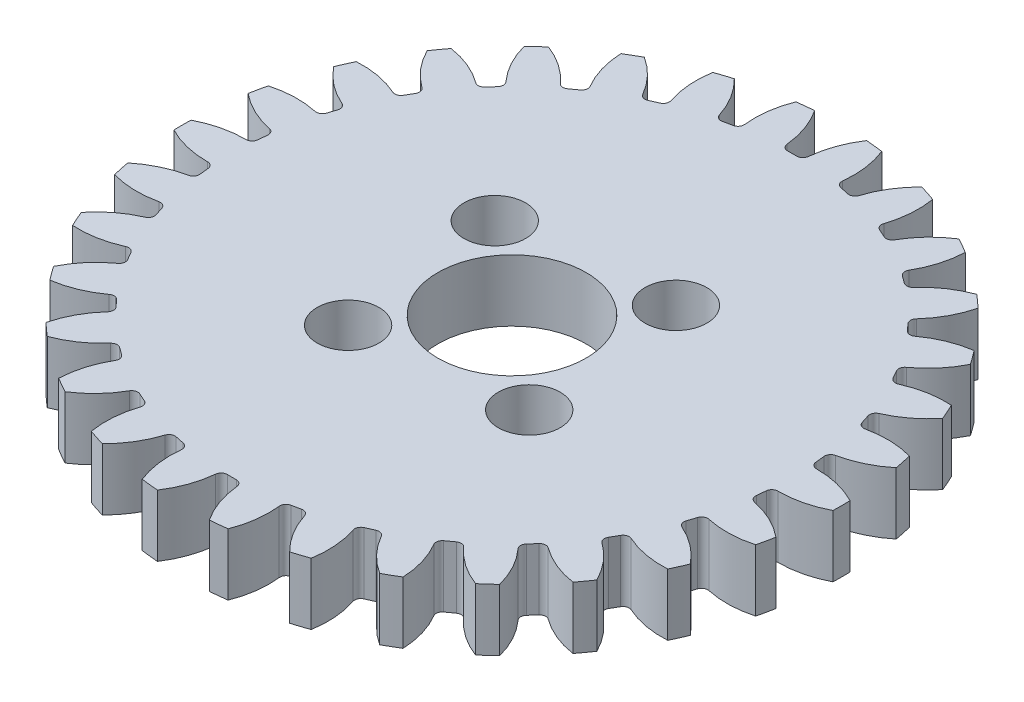
SolidWorks part; units mm, degrees
ref_plane "Alzado" through (0, 0, 0) normal (0, 0, 1) x (1, 0, 0)
ref_plane "Planta" through (0, 0, 0) normal (0, 1, 0) x (1, 0, 0)
ref_plane "Vista lateral" through (0, 0, 0) normal (1, 0, 0) x (0, 0, -1)
sketch "Croquis1" plane through (0, 0, 0) normal (0, 1, 0) x (1, 0, 0)
  line L0 (0, 0) -> (0, 24.4895) construction
  line L1 (-0.2199, 13.6) -> (0.2199, 13.6)
  line L2 (2.6125, 13.3485) -> (3.0427, 13.2571)
  line L3 (5.3308, 12.5136) -> (5.7325, 12.3348)
  line L4 (7.816, 11.1319) -> (8.1718, 10.8734)
  line L5 (9.9596, 9.2636) -> (10.2539, 8.9368)
  line L6 (11.668, 6.9904) -> (11.8879, 6.6096)
  line L7 (12.8664, 4.4117) -> (13.0023, 3.9935)
  line L8 (13.5025, 1.6403) -> (13.5485, 1.2029)
  line L9 (13.5485, -1.2029) -> (13.5025, -1.6403)
  line L10 (13.0023, -3.9935) -> (12.8664, -4.4117)
  line L11 (11.8879, -6.6096) -> (11.668, -6.9904)
  line L12 (10.2539, -8.9368) -> (9.9596, -9.2636)
  line L13 (8.1718, -10.8734) -> (7.816, -11.1319)
  line L14 (5.7325, -12.3348) -> (5.3308, -12.5136)
  line L15 (3.0427, -13.2571) -> (2.6125, -13.3485)
  line L16 (0.2199, -13.6) -> (-0.2199, -13.6)
  line L17 (-2.6125, -13.3485) -> (-3.0427, -13.2571)
  line L18 (-5.3308, -12.5136) -> (-5.7325, -12.3348)
  line L19 (-7.816, -11.1319) -> (-8.1718, -10.8734)
  line L20 (-9.9596, -9.2636) -> (-10.2539, -8.9368)
  line L21 (-11.668, -6.9904) -> (-11.8879, -6.6096)
  line L22 (-12.8664, -4.4117) -> (-13.0023, -3.9935)
  line L23 (-13.5025, -1.6403) -> (-13.5485, -1.2029)
  line L24 (-13.5485, 1.2029) -> (-13.5025, 1.6403)
  line L25 (-13.0023, 3.9935) -> (-12.8664, 4.4117)
  line L26 (-11.8879, 6.6096) -> (-11.668, 6.9904)
  line L27 (-10.2539, 8.9368) -> (-9.9596, 9.2636)
  line L28 (-8.1718, 10.8734) -> (-7.816, 11.1319)
  line L29 (-5.7325, 12.3348) -> (-5.3308, 12.5136)
  line L30 (-3.0427, 13.2571) -> (-2.6125, 13.3485)
  line L31 (0, 0) -> (0, -0.9994) construction
  line L32 (0, 0) -> (10.8733, 0) construction
  circle A0 centre (0, 0) radius 16
  arc A1 (0.5184, 13.8707) -> (2.08, 16.88) centre (5.0567, 13.4256) cw
  arc A2 (-0.5184, 13.8707) -> (-2.08, 16.88) centre (-5.0567, 13.4256) ccw
  arc A3 (-2.08, 16.88) -> (2.08, 16.88) centre (0, -0.9994) cw
  arc A4 (0.2199, 13.6) -> (0.5184, 13.8707) centre (0.2199, 13.9) ccw
  arc A5 (-0.5184, 13.8707) -> (-0.2199, 13.6) centre (-0.2199, 13.9) ccw
  arc A6 (1.475, 16.9436) -> (5.5441, 16.0787) centre (-0.2078, -0.9776) cw
  arc A7 (3.391, 13.4598) -> (5.5441, 16.0787) centre (7.7375, 12.0809) cw
  arc A8 (3.0427, 13.2571) -> (3.391, 13.4598) centre (3.105, 13.5505) ccw
  arc A9 (2.3768, 13.6754) -> (2.6125, 13.3485) centre (2.6749, 13.642) ccw
  arc A10 (2.3768, 13.6754) -> (1.475, 16.9436) centre (-2.1548, 14.1835) ccw
  arc A11 (4.9655, 16.2667) -> (8.7659, 14.5746) centre (-0.4065, -0.913) cw
  arc A12 (6.1153, 12.4607) -> (8.7659, 14.5746) centre (10.0802, 10.2081) cw
  arc A13 (5.7325, 12.3348) -> (6.1153, 12.4607) centre (5.8545, 12.6089) ccw
  arc A14 (5.1681, 12.8824) -> (5.3308, 12.5136) centre (5.4528, 12.7877) ccw
  arc A15 (5.1681, 12.8824) -> (4.9655, 16.2667) centre (0.8412, 14.3216) ccw
  arc A16 (8.2391, 14.8788) -> (11.6046, 12.4336) centre (-0.5874, -0.8085) cw
  arc A17 (8.5724, 10.9169) -> (11.6046, 12.4336) centre (11.9823, 7.8893) cw
  arc A18 (8.1718, 10.8734) -> (8.5724, 10.9169) centre (8.3481, 11.1161) ccw
  arc A19 (7.7336, 11.5264) -> (7.816, 11.1319) centre (7.9923, 11.3746) ccw
  arc A20 (7.7336, 11.5264) -> (8.2391, 14.8788) centre (3.8004, 13.8337) ccw
  arc A21 (11.1525, 12.8407) -> (13.9361, 9.7492) centre (-0.7427, -0.6687) cw
  arc A22 (10.6549, 8.896) -> (13.9361, 9.7492) centre (13.3607, 5.2256) cw
  arc A23 (10.2539, 8.9368) -> (10.6549, 8.896) centre (10.4768, 9.1375) ccw
  arc A24 (9.961, 9.6666) -> (9.9596, 9.2636) centre (10.1826, 9.4643) ccw
  arc A25 (9.961, 9.6666) -> (11.1525, 12.8407) centre (6.5936, 12.7413) ccw
  arc A26 (13.5785, 10.2413) -> (15.6585, 6.6387) centre (-0.8655, -0.4997) cw
  arc A27 (12.2716, 6.4864) -> (15.6585, 6.6387) centre (14.1552, 2.3336) cw
  arc A28 (11.8879, 6.6096) -> (12.2716, 6.4864) centre (12.1477, 6.7596) ccw
  arc A29 (11.7532, 7.3843) -> (11.668, 6.9904) centre (11.9278, 7.1404) ccw
  arc A30 (11.7532, 7.3843) -> (13.5785, 10.2413) centre (9.0986, 11.092) ccw
  arc A31 (15.4111, 7.1944) -> (16.6966, 3.238) centre (-0.9505, -0.3088) cw
  arc A32 (13.352, 3.7932) -> (16.6966, 3.238) centre (14.3311, -0.6604) cw
  arc A33 (13.0023, 3.9935) -> (13.352, 3.7932) centre (13.2876, 4.0862) ccw
  arc A34 (13.0316, 4.7794) -> (12.8664, 4.4117) centre (13.1517, 4.5044) ccw
  arc A35 (13.0316, 4.7794) -> (15.4111, 7.1944) centre (11.2059, 8.9579) ccw
  arc A36 (16.5701, 3.833) -> (17.0049, -0.3042) centre (-0.9939, -0.1045) cw
  arc A37 (13.8489, 0.9343) -> (17.0049, -0.3042) centre (13.8806, -3.6256) cw
  arc A38 (13.5485, 1.2029) -> (13.8489, 0.9343) centre (13.8468, 1.2343) ccw
  arc A39 (13.7405, 1.9655) -> (13.5025, 1.6403) centre (13.8009, 1.6716) ccw
  arc A40 (13.7405, 1.9655) -> (16.5701, 3.833) centre (12.8235, 6.4323) ccw
  arc A41 (17.0049, 0.3042) -> (16.5701, -3.833) centre (-0.9939, 0.1045) cw
  arc A42 (13.7405, -1.9655) -> (16.5701, -3.833) centre (12.8235, -6.4323) cw
  arc A43 (13.5025, -1.6403) -> (13.7405, -1.9655) centre (13.8009, -1.6716) ccw
  arc A44 (13.8489, -0.9343) -> (13.5485, -1.2029) centre (13.8468, -1.2343) ccw
  arc A45 (13.8489, -0.9343) -> (17.0049, 0.3042) centre (13.8806, 3.6256) ccw
  arc A46 (16.6966, -3.238) -> (15.4111, -7.1944) centre (-0.9505, 0.3088) cw
  arc A47 (13.0316, -4.7794) -> (15.4111, -7.1944) centre (11.2059, -8.9579) cw
  arc A48 (12.8664, -4.4117) -> (13.0316, -4.7794) centre (13.1517, -4.5044) ccw
  arc A49 (13.352, -3.7932) -> (13.0023, -3.9935) centre (13.2876, -4.0862) ccw
  arc A50 (13.352, -3.7932) -> (16.6966, -3.238) centre (14.3311, 0.6604) ccw
  arc A51 (15.6585, -6.6387) -> (13.5785, -10.2413) centre (-0.8655, 0.4997) cw
  arc A52 (11.7532, -7.3843) -> (13.5785, -10.2413) centre (9.0986, -11.092) cw
  arc A53 (11.668, -6.9904) -> (11.7532, -7.3843) centre (11.9278, -7.1404) ccw
  arc A54 (12.2716, -6.4864) -> (11.8879, -6.6096) centre (12.1477, -6.7596) ccw
  arc A55 (12.2716, -6.4864) -> (15.6585, -6.6387) centre (14.1552, -2.3336) ccw
  arc A56 (13.9361, -9.7492) -> (11.1525, -12.8407) centre (-0.7427, 0.6687) cw
  arc A57 (9.961, -9.6666) -> (11.1525, -12.8407) centre (6.5936, -12.7413) cw
  arc A58 (9.9596, -9.2636) -> (9.961, -9.6666) centre (10.1826, -9.4643) ccw
  arc A59 (10.6549, -8.896) -> (10.2539, -8.9368) centre (10.4768, -9.1375) ccw
  arc A60 (10.6549, -8.896) -> (13.9361, -9.7492) centre (13.3607, -5.2256) ccw
  arc A61 (11.6046, -12.4336) -> (8.2391, -14.8788) centre (-0.5874, 0.8085) cw
  arc A62 (7.7336, -11.5264) -> (8.2391, -14.8788) centre (3.8004, -13.8337) cw
  arc A63 (7.816, -11.1319) -> (7.7336, -11.5264) centre (7.9923, -11.3746) ccw
  arc A64 (8.5724, -10.9169) -> (8.1718, -10.8734) centre (8.3481, -11.1161) ccw
  arc A65 (8.5724, -10.9169) -> (11.6046, -12.4336) centre (11.9823, -7.8893) ccw
  arc A66 (8.7659, -14.5746) -> (4.9655, -16.2667) centre (-0.4065, 0.913) cw
  arc A67 (5.1681, -12.8824) -> (4.9655, -16.2667) centre (0.8412, -14.3216) cw
  arc A68 (5.3308, -12.5136) -> (5.1681, -12.8824) centre (5.4528, -12.7877) ccw
  arc A69 (6.1153, -12.4607) -> (5.7325, -12.3348) centre (5.8545, -12.6089) ccw
  arc A70 (6.1153, -12.4607) -> (8.7659, -14.5746) centre (10.0802, -10.2081) ccw
  arc A71 (5.5441, -16.0787) -> (1.475, -16.9436) centre (-0.2078, 0.9776) cw
  arc A72 (2.3768, -13.6754) -> (1.475, -16.9436) centre (-2.1548, -14.1835) cw
  arc A73 (2.6125, -13.3485) -> (2.3768, -13.6754) centre (2.6749, -13.642) ccw
  arc A74 (3.391, -13.4598) -> (3.0427, -13.2571) centre (3.105, -13.5505) ccw
  arc A75 (3.391, -13.4598) -> (5.5441, -16.0787) centre (7.7375, -12.0809) ccw
  arc A76 (2.08, -16.88) -> (-2.08, -16.88) centre (0, 0.9994) cw
  arc A77 (-0.5184, -13.8707) -> (-2.08, -16.88) centre (-5.0567, -13.4256) cw
  arc A78 (-0.2199, -13.6) -> (-0.5184, -13.8707) centre (-0.2199, -13.9) ccw
  arc A79 (0.5184, -13.8707) -> (0.2199, -13.6) centre (0.2199, -13.9) ccw
  arc A80 (0.5184, -13.8707) -> (2.08, -16.88) centre (5.0567, -13.4256) ccw
  arc A81 (-1.475, -16.9436) -> (-5.5441, -16.0787) centre (0.2078, 0.9776) cw
  arc A82 (-3.391, -13.4598) -> (-5.5441, -16.0787) centre (-7.7375, -12.0809) cw
  arc A83 (-3.0427, -13.2571) -> (-3.391, -13.4598) centre (-3.105, -13.5505) ccw
  arc A84 (-2.3768, -13.6754) -> (-2.6125, -13.3485) centre (-2.6749, -13.642) ccw
  arc A85 (-2.3768, -13.6754) -> (-1.475, -16.9436) centre (2.1548, -14.1835) ccw
  arc A86 (-4.9655, -16.2667) -> (-8.7659, -14.5746) centre (0.4065, 0.913) cw
  arc A87 (-6.1153, -12.4607) -> (-8.7659, -14.5746) centre (-10.0802, -10.2081) cw
  arc A88 (-5.7325, -12.3348) -> (-6.1153, -12.4607) centre (-5.8545, -12.6089) ccw
  arc A89 (-5.1681, -12.8824) -> (-5.3308, -12.5136) centre (-5.4528, -12.7877) ccw
  arc A90 (-5.1681, -12.8824) -> (-4.9655, -16.2667) centre (-0.8412, -14.3216) ccw
  arc A91 (-8.2391, -14.8788) -> (-11.6046, -12.4336) centre (0.5874, 0.8085) cw
  arc A92 (-8.5724, -10.9169) -> (-11.6046, -12.4336) centre (-11.9823, -7.8893) cw
  arc A93 (-8.1718, -10.8734) -> (-8.5724, -10.9169) centre (-8.3481, -11.1161) ccw
  arc A94 (-7.7336, -11.5264) -> (-7.816, -11.1319) centre (-7.9923, -11.3746) ccw
  arc A95 (-7.7336, -11.5264) -> (-8.2391, -14.8788) centre (-3.8004, -13.8337) ccw
  arc A96 (-11.1525, -12.8407) -> (-13.9361, -9.7492) centre (0.7427, 0.6687) cw
  arc A97 (-10.6549, -8.896) -> (-13.9361, -9.7492) centre (-13.3607, -5.2256) cw
  arc A98 (-10.2539, -8.9368) -> (-10.6549, -8.896) centre (-10.4768, -9.1375) ccw
  arc A99 (-9.961, -9.6666) -> (-9.9596, -9.2636) centre (-10.1826, -9.4643) ccw
  arc A100 (-9.961, -9.6666) -> (-11.1525, -12.8407) centre (-6.5936, -12.7413) ccw
  arc A101 (-13.5785, -10.2413) -> (-15.6585, -6.6387) centre (0.8655, 0.4997) cw
  arc A102 (-12.2716, -6.4864) -> (-15.6585, -6.6387) centre (-14.1552, -2.3336) cw
  arc A103 (-11.8879, -6.6096) -> (-12.2716, -6.4864) centre (-12.1477, -6.7596) ccw
  arc A104 (-11.7532, -7.3843) -> (-11.668, -6.9904) centre (-11.9278, -7.1404) ccw
  arc A105 (-11.7532, -7.3843) -> (-13.5785, -10.2413) centre (-9.0986, -11.092) ccw
  arc A106 (-15.4111, -7.1944) -> (-16.6966, -3.238) centre (0.9505, 0.3088) cw
  arc A107 (-13.352, -3.7932) -> (-16.6966, -3.238) centre (-14.3311, 0.6604) cw
  arc A108 (-13.0023, -3.9935) -> (-13.352, -3.7932) centre (-13.2876, -4.0862) ccw
  arc A109 (-13.0316, -4.7794) -> (-12.8664, -4.4117) centre (-13.1517, -4.5044) ccw
  arc A110 (-13.0316, -4.7794) -> (-15.4111, -7.1944) centre (-11.2059, -8.9579) ccw
  arc A111 (-16.5701, -3.833) -> (-17.0049, 0.3042) centre (0.9939, 0.1045) cw
  arc A112 (-13.8489, -0.9343) -> (-17.0049, 0.3042) centre (-13.8806, 3.6256) cw
  arc A113 (-13.5485, -1.2029) -> (-13.8489, -0.9343) centre (-13.8468, -1.2343) ccw
  arc A114 (-13.7405, -1.9655) -> (-13.5025, -1.6403) centre (-13.8009, -1.6716) ccw
  arc A115 (-13.7405, -1.9655) -> (-16.5701, -3.833) centre (-12.8235, -6.4323) ccw
  arc A116 (-17.0049, -0.3042) -> (-16.5701, 3.833) centre (0.9939, -0.1045) cw
  arc A117 (-13.7405, 1.9655) -> (-16.5701, 3.833) centre (-12.8235, 6.4323) cw
  arc A118 (-13.5025, 1.6403) -> (-13.7405, 1.9655) centre (-13.8009, 1.6716) ccw
  arc A119 (-13.8489, 0.9343) -> (-13.5485, 1.2029) centre (-13.8468, 1.2343) ccw
  arc A120 (-13.8489, 0.9343) -> (-17.0049, -0.3042) centre (-13.8806, -3.6256) ccw
  arc A121 (-16.6966, 3.238) -> (-15.4111, 7.1944) centre (0.9505, -0.3088) cw
  arc A122 (-13.0316, 4.7794) -> (-15.4111, 7.1944) centre (-11.2059, 8.9579) cw
  arc A123 (-12.8664, 4.4117) -> (-13.0316, 4.7794) centre (-13.1517, 4.5044) ccw
  arc A124 (-13.352, 3.7932) -> (-13.0023, 3.9935) centre (-13.2876, 4.0862) ccw
  arc A125 (-13.352, 3.7932) -> (-16.6966, 3.238) centre (-14.3311, -0.6604) ccw
  arc A126 (-15.6585, 6.6387) -> (-13.5785, 10.2413) centre (0.8655, -0.4997) cw
  arc A127 (-11.7532, 7.3843) -> (-13.5785, 10.2413) centre (-9.0986, 11.092) cw
  arc A128 (-11.668, 6.9904) -> (-11.7532, 7.3843) centre (-11.9278, 7.1404) ccw
  arc A129 (-12.2716, 6.4864) -> (-11.8879, 6.6096) centre (-12.1477, 6.7596) ccw
  arc A130 (-12.2716, 6.4864) -> (-15.6585, 6.6387) centre (-14.1552, 2.3336) ccw
  arc A131 (-13.9361, 9.7492) -> (-11.1525, 12.8407) centre (0.7427, -0.6687) cw
  arc A132 (-9.961, 9.6666) -> (-11.1525, 12.8407) centre (-6.5936, 12.7413) cw
  arc A133 (-9.9596, 9.2636) -> (-9.961, 9.6666) centre (-10.1826, 9.4643) ccw
  arc A134 (-10.6549, 8.896) -> (-10.2539, 8.9368) centre (-10.4768, 9.1375) ccw
  arc A135 (-10.6549, 8.896) -> (-13.9361, 9.7492) centre (-13.3607, 5.2256) ccw
  arc A136 (-11.6046, 12.4336) -> (-8.2391, 14.8788) centre (0.5874, -0.8085) cw
  arc A137 (-7.7336, 11.5264) -> (-8.2391, 14.8788) centre (-3.8004, 13.8337) cw
  arc A138 (-7.816, 11.1319) -> (-7.7336, 11.5264) centre (-7.9923, 11.3746) ccw
  arc A139 (-8.5724, 10.9169) -> (-8.1718, 10.8734) centre (-8.3481, 11.1161) ccw
  arc A140 (-8.5724, 10.9169) -> (-11.6046, 12.4336) centre (-11.9823, 7.8893) ccw
  arc A141 (-8.7659, 14.5746) -> (-4.9655, 16.2667) centre (0.4065, -0.913) cw
  arc A142 (-5.1681, 12.8824) -> (-4.9655, 16.2667) centre (-0.8412, 14.3216) cw
  arc A143 (-5.3308, 12.5136) -> (-5.1681, 12.8824) centre (-5.4528, 12.7877) ccw
  arc A144 (-6.1153, 12.4607) -> (-5.7325, 12.3348) centre (-5.8545, 12.6089) ccw
  arc A145 (-6.1153, 12.4607) -> (-8.7659, 14.5746) centre (-10.0802, 10.2081) ccw
  arc A146 (-5.5441, 16.0787) -> (-1.475, 16.9436) centre (0.2078, -0.9776) cw
  arc A147 (-2.3768, 13.6754) -> (-1.475, 16.9436) centre (2.1548, 14.1835) cw
  arc A148 (-2.6125, 13.3485) -> (-2.3768, 13.6754) centre (-2.6749, 13.642) ccw
  arc A149 (-3.391, 13.4598) -> (-3.0427, 13.2571) centre (-3.105, 13.5505) ccw
  arc A150 (-3.391, 13.4598) -> (-5.5441, 16.0787) centre (-7.7375, 12.0809) ccw
  circle A151 centre (3.56, 4.3962) radius 1.5
  circle A152 centre (-4.3962, 3.56) radius 1.5
  circle A153 centre (4.3962, -3.56) radius 1.5
  circle A154 centre (-3.56, -4.3962) radius 1.5
  circle A155 centre (0, 0) radius 3.6
  point P11 (0, 13.6)
  point P14 (0.5, 13.6)
  point P17 (-0.5, 13.6)
  dimension "D1" = 32
  dimension "D6" = 4.56
  dimension "D7" = 18
  dimension "D8" = 0.3
  dimension "D11" = 7.2115
  dimension "D12" = 7.2
  dimension "D2" = 0.5
  dimension "D3" = 13.6
  dimension "D4" = 1.58
  dimension "D5" = 3.28
  dimension "D10" = 0.9994
  dimension "D9" = 30
extrude "Saliente-Extruir1" add sketch "Croquis1" along normal blind 3 contours A149 A150 A0 A142 A143 L29 A144 A145 A137 A138 L28 A139 A140 A132 A133 L27 A134 A135 A127 A128 L26 A129 A130 A122 A123 L25 A124 A125 A117 A118 L24 A119 A120 A112 A113 L23 A114 A115 A107 A108 L22 A109 A110
